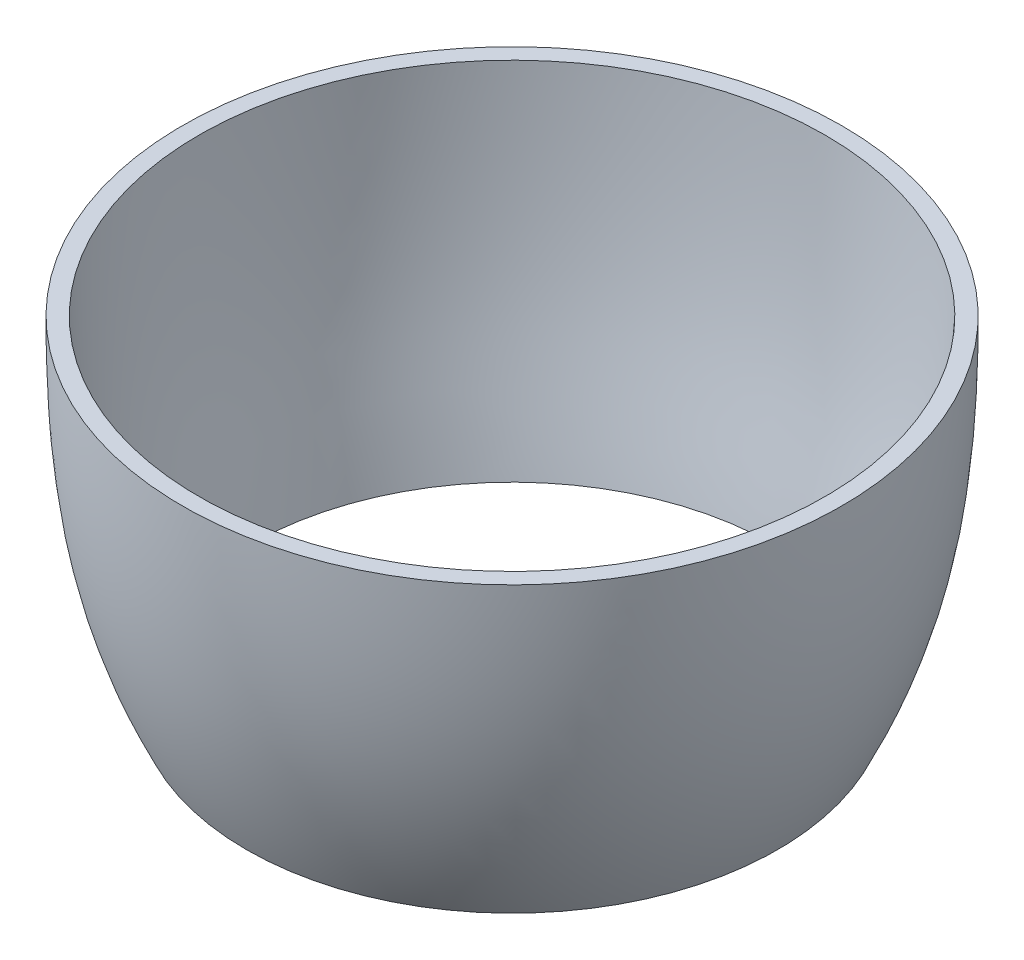
SolidWorks part; units mm, degrees
ref_plane "Front Plane" through (0, 0, 0) normal (0, 0, 1) x (1, 0, 0)
ref_plane "Top Plane" through (0, 0, 0) normal (0, 1, 0) x (1, 0, 0)
ref_plane "Right Plane" through (0, 0, 0) normal (1, 0, 0) x (0, 0, -1)
sketch "Sketch2" plane through (0, 0, 0) normal (1, 0, 0) x (0, 0, -1)
  line L2 (25.4, 25.4) -> (24.13, 25.4)
  line L3 (20.2178, 0) -> (20.4718, 0)
  line L4 (0, 0) -> (0, 25.4) construction
  spline S0 degree 3 poles (25.4, 25.4) (25.4, 20.4616) (24.9825, 11.6705) (22.1136, 3.3667) (20.4718, 0) knots 0 0 0 0 0.569345 1 1 1 1
  spline S1 degree 3 poles (24.13, 25.4) (23.8411, 20.3625) (23.0732, 11.7768) (20.9042, 3.4588) (20.2178, 0) knots 0 0 0 0 0.588812 1 1 1 1
  dimension "D1" = 1.27
  dimension "D2" = 25.4
  dimension "D3" = 0.254
revolve "Revolve1" add sketch "Sketch2" angle 360 about L4
